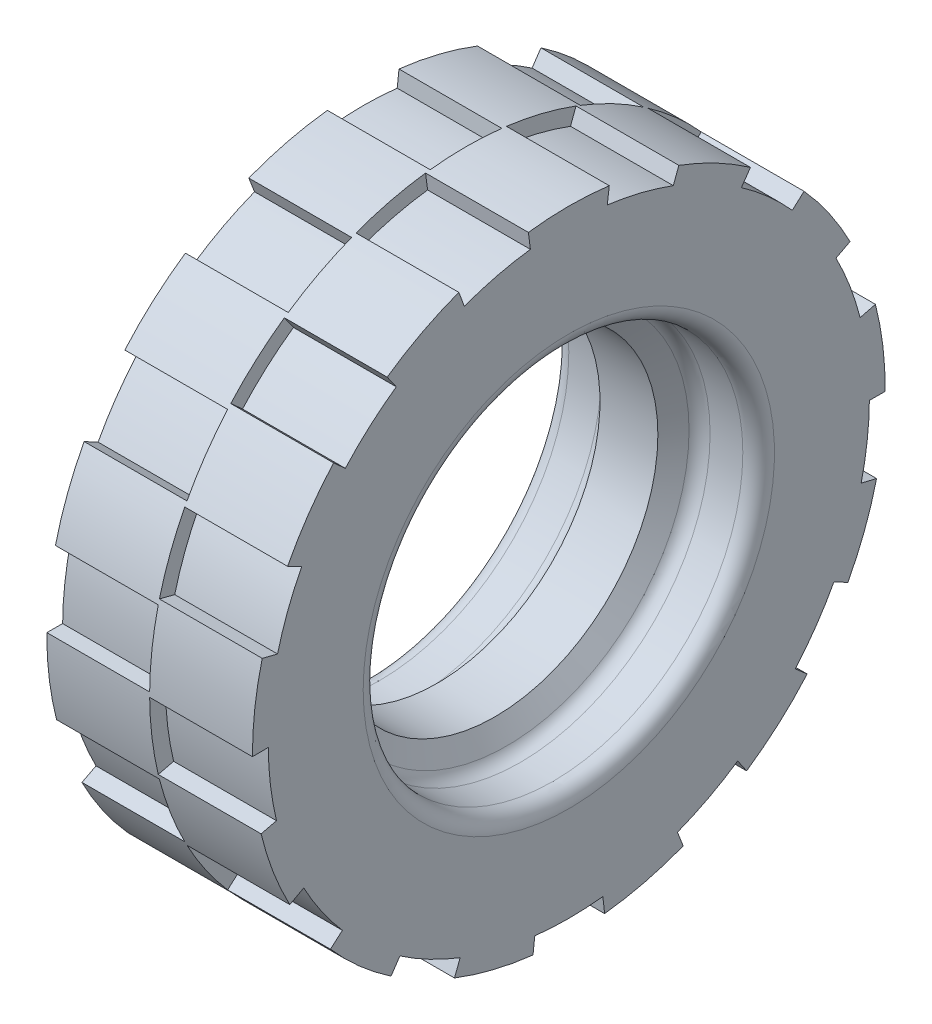
SolidWorks part; units mm, degrees
material "BUTYL"
ref_plane "Front" through (0, 0, 0) normal (0, 0, 1) x (1, 0, 0)
ref_plane "Top" through (0, 0, 0) normal (0, 1, 0) x (1, 0, 0)
ref_plane "Right" through (0, 0, 0) normal (1, 0, 0) x (0, 0, -1)
sketch "Sketch1" plane through (0, 0, 0) normal (0, 0, 1) x (1, 0, 0)
  line L0 (0, 0) -> (0, 10) construction
  line L1 (-3.25, 10) -> (3.25, 10)
  line L2 (0, 0) -> (6.4758, 0) construction
  line L3 (3.25, 10) -> (3.25, 6)
  line L4 (3.25, 6) -> (1.435, 6)
  line L5 (1.435, 6) -> (0.915, 5.15)
  line L6 (-0.915, 5.15) -> (0.915, 5.15)
  line L7 (-1.435, 6) -> (-0.915, 5.15)
  line L8 (-3.25, 6) -> (-1.435, 6)
  line L9 (-3.25, 10) -> (-3.25, 6)
  point P10 (0, 5.15)
  dimension "D1" = 3.25
  dimension "D2" = 20
  dimension "D3" = 12
  dimension "D4" = 10.3
  dimension "D5" = 2.87
  dimension "D6" = 1.83
revolve "Revolve1" add sketch "Sketch1" angle 360 about L2
sketch "Sketch2" plane through (-3.25, 0, 0) normal (-1, 0, 0) x (0, 0, 1)
  line L0 (0, 0) -> (0, 14.0412) construction
  line L1 (-1.0754, 9.4389) -> (-1.132, 9.9357)
  line L2 (1.0754, 9.4389) -> (1.132, 9.9357)
  circle A1 centre (0, 0) radius 10 construction
  circle A2 centre (0, 0) radius 9.5
  arc A3 (1.0754, 9.4389) -> (-1.0754, 9.4389) centre (0, 0) ccw
  arc A4 (1.132, 9.9357) -> (-1.132, 9.9357) centre (0, 0) ccw
  dimension "D1" = 0.5
extrude "Cut-Extrude1" cut sketch "Sketch2" against normal blind 3.25
pattern_circular "CirPattern1" count 13 over 360 about axis through (0, 0, 0) along (1, 0, 0) of "Cut-Extrude1"
sketch "Sketch3" plane through (3.25, 0, 0) normal (1, 0, 0) x (0, 0, -1)
  line L0 (-3.3029, 8.9074) -> (-3.4767, 9.3762)
  line L1 (0, 0) -> (-3.326, 13.4955) construction
  line L2 (-1.2145, 9.422) -> (-1.2784, 9.9179)
  circle A0 centre (0, 0) radius 10 construction
  arc A1 (-1.2784, 9.9179) -> (-3.4767, 9.3762) centre (0, 0) ccw
  arc A2 (-1.2145, 9.422) -> (-3.3029, 8.9074) centre (0, 0) ccw
  circle A3 centre (0, 0) radius 9.5 construction
  circle A4 centre (0, 0) radius 10 construction
  dimension "D1" = 0.5
extrude "Cut-Extrude2" cut sketch "Sketch3" against normal blind 3.25
pattern_circular "CirPattern2" count 13 over 360 about axis through (0, 0, 0) along (1, 0, 0) of "Cut-Extrude2"
fillet "Fillet1" radius 0.5 4 edges at (3.25, 0, 6) (-3.25, 0, 6) (1.435, 0, 6) (-1.435, 0, 6)
